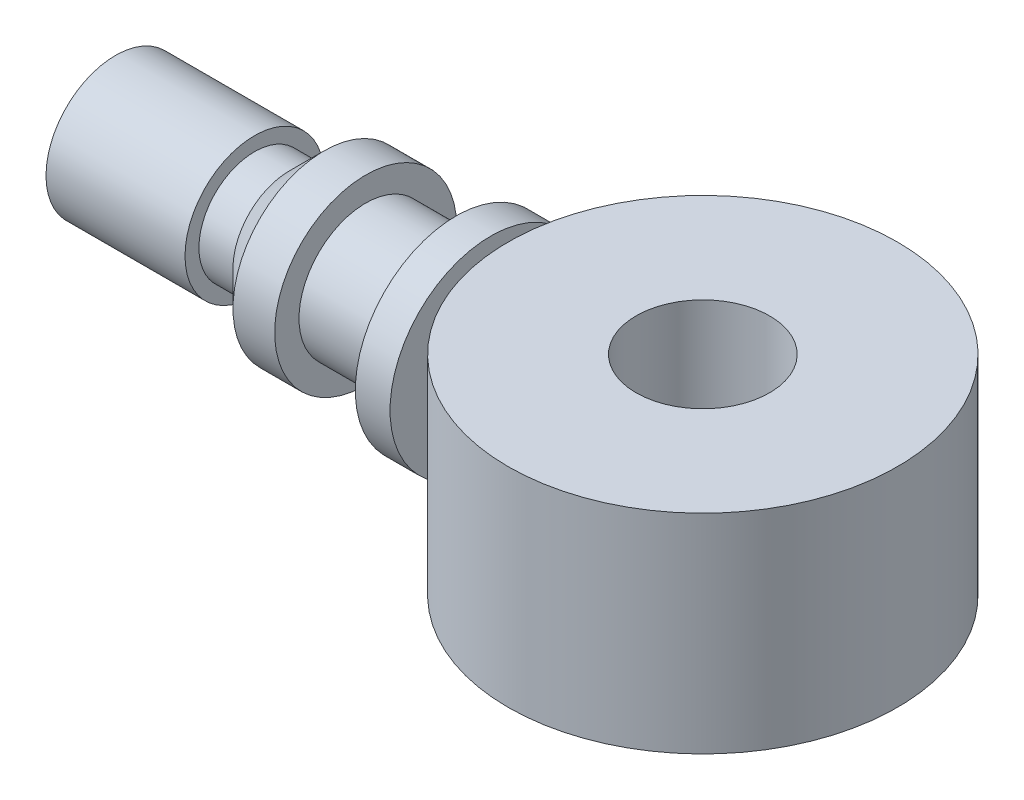
SolidWorks part; units mm, degrees
ref_plane "前视基准面" through (0, 0, 0) normal (0, 0, 1) x (1, 0, 0)
ref_plane "上视基准面" through (0, 0, 0) normal (0, 1, 0) x (1, 0, 0)
ref_plane "右视基准面" through (0, 0, 0) normal (1, 0, 0) x (0, 0, -1)
ref_plane "基准面4" through (0, -42.25, 0) normal (0, 1, 0) x (1, 0, 0)
sketch "草图1" plane through (0, -42.25, 0) normal (0, 1, 0) x (1, 0, 0)
  line L0 (58.375, 17.125) -> (34.9254, 17.125)
  line L1 (43.5, 17.125) -> (43.5, 13.85)
  line L2 (43.5, 13.85) -> (46.25, 13.85)
  line L3 (46.25, 13.85) -> (46.25, 14.725)
  line L4 (46.25, 14.725) -> (49.5, 14.725)
  line L5 (49.5, 14.725) -> (49.5, 13.5)
  line L6 (49.5, 13.5) -> (50.75, 13.5)
  line L7 (50.75, 13.5) -> (50.75, 15.125)
  line L8 (50.75, 15.125) -> (53.2749, 15.125)
  line L9 (53.2749, 15.125) -> (53.2749, 17.125)
  circle A0 centre (58.375, 17.125) radius 2.4 construction
  circle A1 centre (58.375, 17.125) radius 2.4
  dimension "D1" = 43.5
  dimension "D2" = 50.75
  dimension "D3" = 1.25
  dimension "D4" = 3.25
  dimension "D5" = 2
  dimension "D6" = 1.625
  dimension "D7" = 0.875
revolve "旋转1" add sketch "草图1" angle 360 about L0
sketch "草图2" plane through (0, -46, 0) normal (0, 1, 0) x (1, 0, 0)
  circle A0 centre (58.375, 17.125) radius 2.4 construction
  circle A1 centre (58.375, 17.125) radius 2.4
  circle A2 centre (58.375, 17.125) radius 7
extrude "凸台-拉伸1" add sketch "草图2" along normal up to surface (7.5 mm away)
sketch "草图4" plane through (43.5, 0, 0) normal (-1, 0, 0) x (0, 0, 1)
  circle A0 centre (-17.125, -42.25) radius 2
  circle A1 centre (-17.125, -42.25) radius 3.275
  circle A2 centre (-17.125, -42.25) radius 3.275
  dimension "D2" = 4
  dimension "D1" = 0
extrude "凸台-拉伸3" add sketch "草图4" along normal blind 1.25 contours A0
sketch "草图5" plane through (42.25, 0, 0) normal (-1, 0, 0) x (0, 0, 1)
  circle A0 centre (-17.125, -42.25) radius 2.5
  circle A1 centre (-17.125, -42.25) radius 2
  circle A2 centre (-17.125, -42.25) radius 2
  circle M3 centre (-17.125, -42.25) radius 2
  dimension "D2" = 5
  dimension "D1" = 0
extrude "凸台-拉伸4" add sketch "草图5" along normal blind 5 contours M3 | A0 M3
chamfer "倒角1" distance 1.25 angle 45 1 edges at (43.5, -42.25, -20.4)
